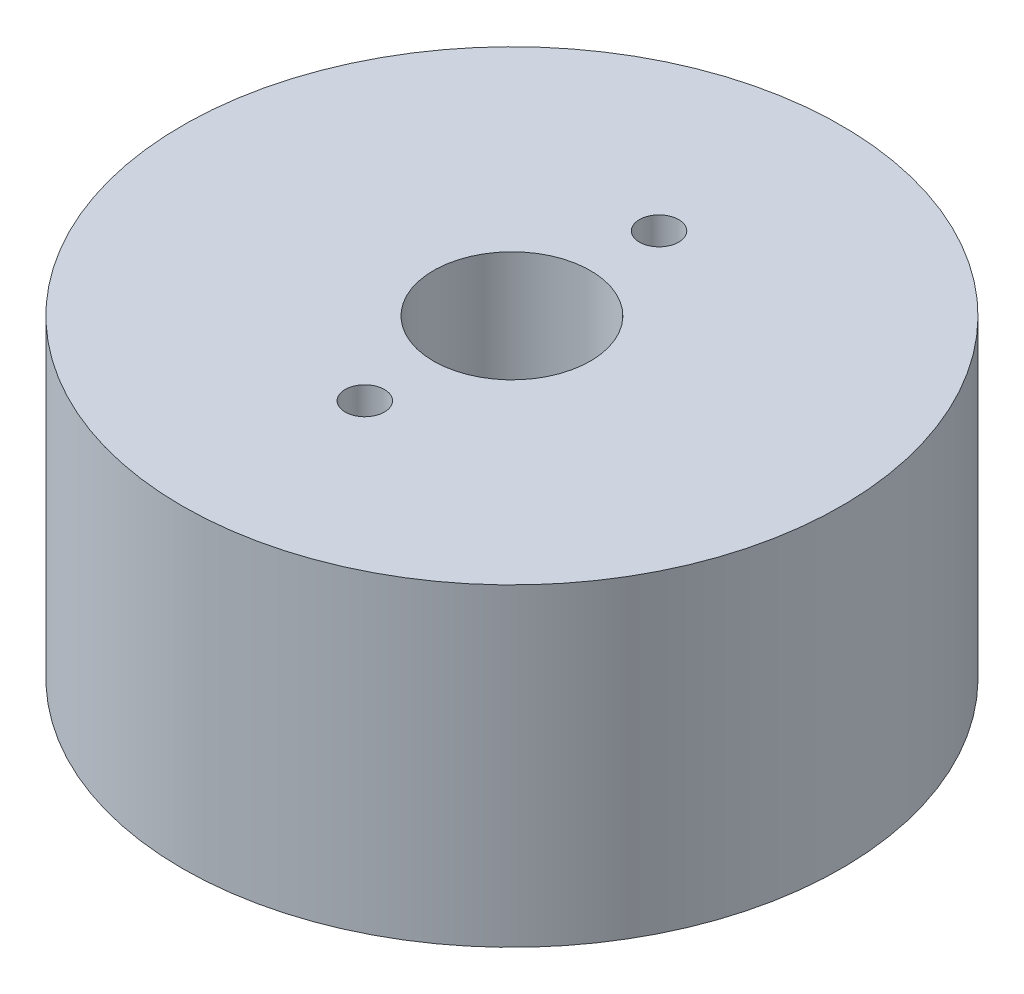
SolidWorks part; units mm, degrees
ref_plane "前视基准面" through (0, 0, 0) normal (0, 0, 1) x (1, 0, 0)
ref_plane "上视基准面" through (0, 0, 0) normal (0, 1, 0) x (1, 0, 0)
ref_plane "右视基准面" through (0, 0, 0) normal (1, 0, 0) x (0, 0, -1)
sketch "Sketch1" plane through (0, 0, 0) normal (0, 1, 0) x (1, 0, 0)
  circle A0 centre (0, 0) radius 16.8
  dimension "D1" = 33.6
extrude "Boss-Extrude1" add sketch "Sketch1" along normal blind 16
sketch "Sketch2" plane through (0, 16, 0) normal (0, 1, 0) x (1, 0, 0)
  circle A0 centre (0, 0) radius 4
  dimension "D1" = 8
extrude "Cut-Extrude1" cut sketch "Sketch2" against normal through all
sketch "Sketch3" plane through (0, 16, 0) normal (0, 1, 0) x (1, 0, 0)
  circle A0 centre (0, 7.5) radius 1
  circle A1 centre (0, -7.5) radius 1
  point P2 (0, -7.5)
  point P12 (0, 0)
  dimension "D1" = 2
  dimension "D2" = 7.5
  dimension "D3" = 2
extrude "Cut-Extrude2" cut sketch "Sketch3" against normal blind 5
sketch "Sketch4" plane through (0, 0, 0) normal (0, -1, 0) x (1, 0, 0)
  circle A0 centre (0, 11.25) radius 1.5
  circle A1 centre (11.25, 0) radius 1.5
  circle A2 centre (0, -11.25) radius 1.5
  circle A3 centre (-11.25, 0) radius 1.5
  point P12 (0, 0)
  dimension "D1" = 11.25
  dimension "D2" = 3
  dimension "D3" = 4
extrude "Cut-Extrude3" cut sketch "Sketch4" against normal blind 5
